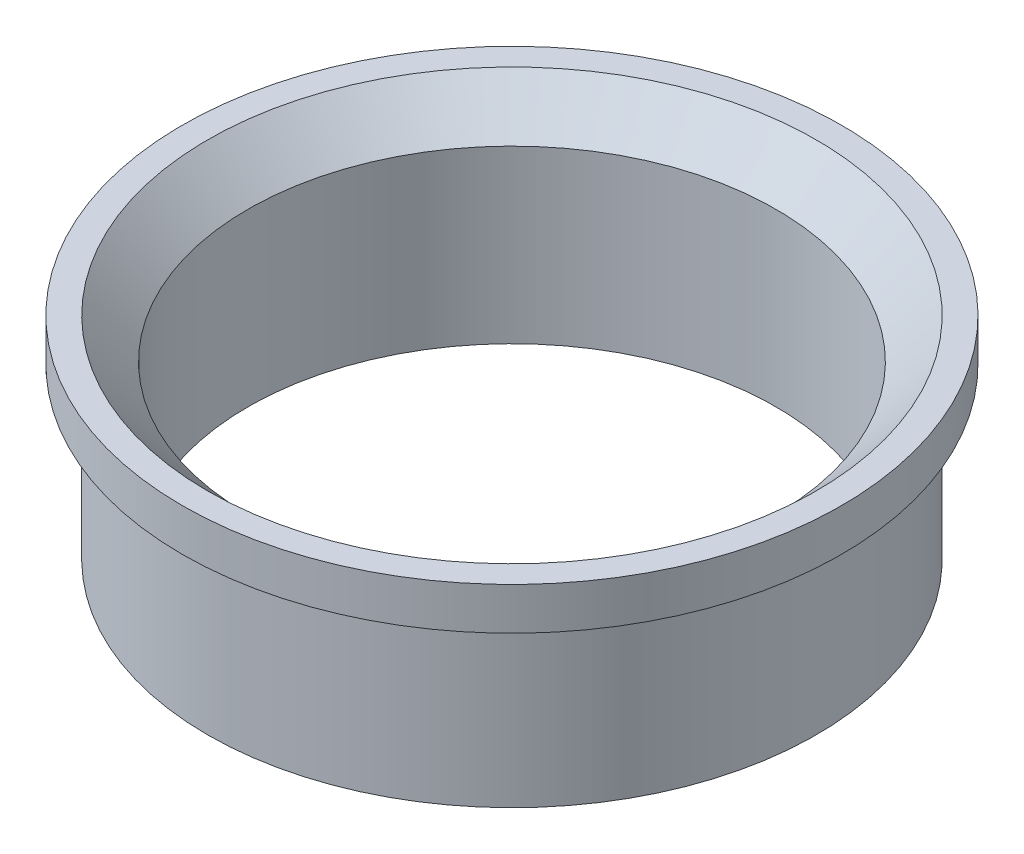
SolidWorks part; units mm, degrees
ref_plane "Front Plane" through (0, 0, 0) normal (0, 0, 1) x (1, 0, 0)
ref_plane "Top Plane" through (0, 0, 0) normal (0, 1, 0) x (1, 0, 0)
ref_plane "Right Plane" through (0, 0, 0) normal (1, 0, 0) x (0, 0, -1)
sketch "Sketch1" plane through (0, 0, 0) normal (0, 0, 1) x (1, 0, 0)
  line L0 (0, 73.4829) -> (0, -76.2617) construction
  line L1 (-72, 40.1377) -> (-78, 40.1377)
  line L2 (-78, 40.1377) -> (-78, 30.1377)
  line L3 (-78, 30.1377) -> (-72, 30.1377)
  line L4 (-72, 30.1377) -> (-72, -9.8623)
  line L5 (-72, -9.8623) -> (-62.5, -9.8623)
  line L6 (-62.5, -9.8623) -> (-62.5, 30.6377)
  line L7 (-62.5, 30.6377) -> (-72, 40.1377)
  dimension "D1" = 72
  dimension "D2" = 78
  dimension "D3" = 72
  dimension "D4" = 62.5
  dimension "D5" = 45
  dimension "D6" = 50
  dimension "D7" = 10
revolve "Revolve1" add sketch "Sketch1" angle 360 about L0
